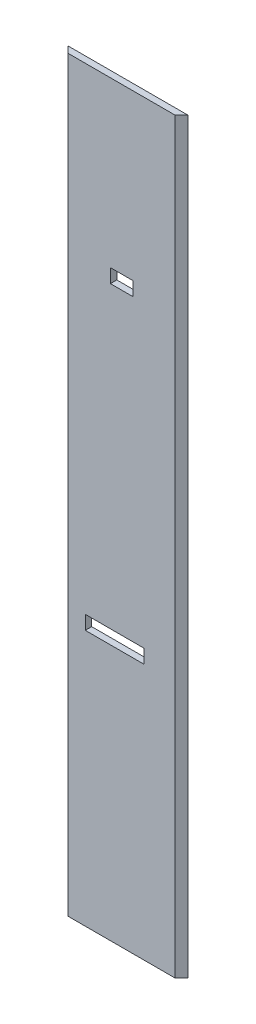
SolidWorks part; units mm, degrees
material "Balsa"
ref_plane "Front Plane" through (0, 0, 0) normal (1, 0, 0) x (0, 1, 0)
ref_plane "Top Plane" through (0, 0, 0) normal (0, 0, 1) x (0, 1, 0)
ref_plane "Right Plane" through (0, 0, 0) normal (0, 1, 0) x (-1, 0, 0)
sketch "Sketch1" plane through (0, 0, 0) normal (0, 0, 1) x (0, 1, 0)
  line L1 (-175, -25) -> (175, -25)
  line L2 (-175, -25) -> (-175, 25)
  line L3 (-175, 25) -> (175, 25)
  line L4 (175, -25) -> (175, 25)
  line L5 (-175, -25) -> (175, 25) construction
  line L6 (-175, 25) -> (175, -25) construction
  point P0 (0, 0)
  dimension "D1" = 350
  dimension "1" = 50
extrude "Boss-Extrude1" add sketch "Sketch1" along normal blind 3
sketch "Sketch2" plane through (0, -175, 0) normal (0, -1, 0) x (1, 0, 0)
  line L2 (-25, 3) -> (25, 3) construction
  line L5 (0, 0) -> (0, 3) construction
  line L9 (-25, 3) -> (-25, 0)
  line L10 (-25, 0) -> (-28, 0)
  line L11 (-25, 3) -> (-28, 0)
  line L12 (25, 3) -> (28, 0)
  line L13 (25, 0) -> (28, 0)
  line L14 (25, 3) -> (25, 0)
  dimension "D1" = 45
extrude "Boss-Extrude2" add sketch "Sketch2" against normal through all
sketch "Sketch3" plane through (0, 0, 0) normal (0, 0, -1) x (1, 0, 0)
  line L0 (0, 175) -> (0, -175) construction
  line L1 (-28, 175) -> (28, 175) construction
  line L2 (28, -175) -> (-28, -175) construction
  line L3 (0, 55) -> (10.5, 55)
  line L4 (10.5, 55) -> (10.5, 48.5)
  line L5 (10.5, 48.5) -> (-17, 48.5)
  line L6 (-17, 48.5) -> (-17, 55)
  line L7 (-17, 55) -> (0, 55)
  line L9 (-5.25, -98) -> (5.25, -98)
  line L10 (-5.25, -98) -> (-5.25, -91.5)
  line L11 (-5.25, -91.5) -> (5.25, -91.5)
  line L12 (5.25, -98) -> (5.25, -91.5)
  line L13 (-5.25, -98) -> (5.25, -91.5) construction
  line L14 (-5.25, -91.5) -> (5.25, -98) construction
  point P10 (0, -94.75)
  dimension "D1" = 10.5
  dimension "D2" = 6.5
  dimension "D3" = 17
  dimension "D4" = 120
  dimension "D5" = 10.5
  dimension "D6" = 6.5
  dimension "D7" = 140
extrude "Cut-Extrude1" cut sketch "Sketch3" against normal blind 10
